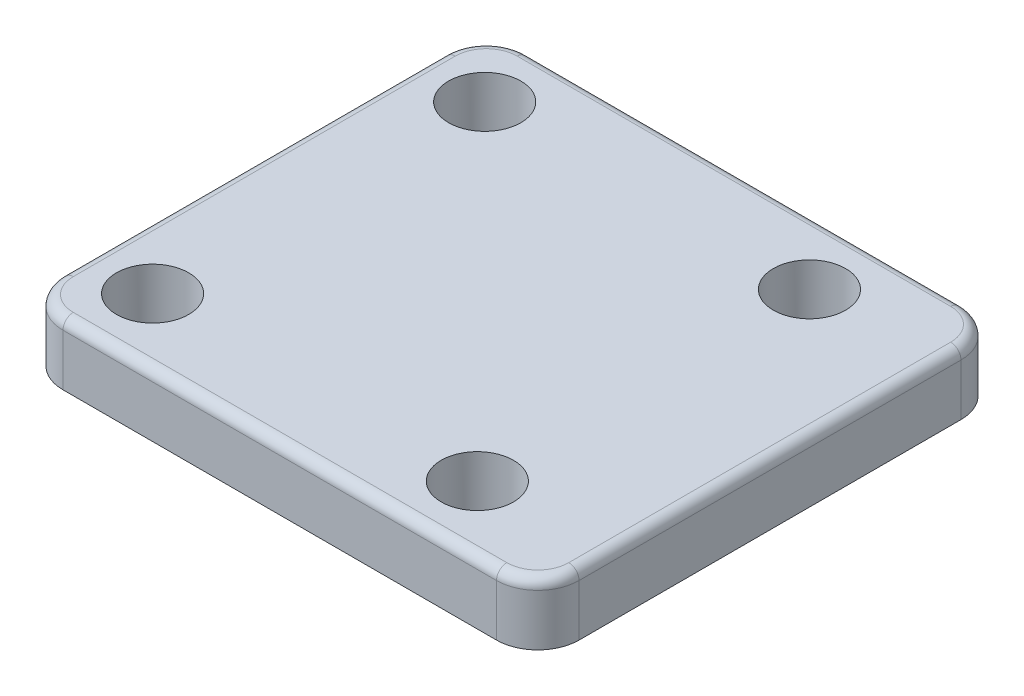
SolidWorks part; units mm, degrees
ref_plane "Front Plane" through (0, 0, 0) normal (0, 0, 1) x (1, 0, 0)
ref_plane "Top Plane" through (0, 0, 0) normal (0, 1, 0) x (1, 0, 0)
ref_plane "Right Plane" through (0, 0, 0) normal (1, 0, 0) x (0, 0, -1)
sketch "Sketch1" plane through (0, 0, 0) normal (0, 1, 0) x (1, 0, 0)
  line L1 (21, -22.5) -> (-21, -22.5)
  line L2 (25, -18.5) -> (25, 18.5)
  line L3 (21, 22.5) -> (-21, 22.5)
  line L4 (-25, -18.5) -> (-25, 18.5)
  line L5 (25, -22.5) -> (-25, 22.5) construction
  line L6 (25, 22.5) -> (-25, -22.5) construction
  arc A0 (-21, -22.5) -> (-25, -18.5) centre (-21, -18.5) cw
  arc A1 (21, -22.5) -> (25, -18.5) centre (21, -18.5) ccw
  arc A2 (25, 18.5) -> (21, 22.5) centre (21, 18.5) ccw
  arc A3 (-21, 22.5) -> (-25, 18.5) centre (-21, 18.5) ccw
  point P0 (0, 0)
  dimension "D3" = 4
  dimension "D1" = 50
  dimension "D2" = 45
extrude "Boss-Extrude1" add sketch "Sketch1" along normal mid plane 6
sketch "Sketch2" plane through (0, 3, 0) normal (0, 1, 0) x (1, 0, 0)
  line L0 (-25, 18.5) -> (-25, -18.5) construction
  line L1 (21, 22.5) -> (-21, 22.5) construction
  line L2 (19, -22.5) -> (-25, -22.5)
  line L3 (19, -22.5) -> (19, 22.5)
  line L4 (19, 22.5) -> (-25, 22.5)
  line L5 (-25, -22.5) -> (-25, 22.5)
  line L6 (19, -22.5) -> (-25, 22.5) construction
  line L7 (19, 22.5) -> (-25, -22.5) construction
  circle A0 centre (-3, 0) radius 22.5 construction
  circle A1 centre (-18.7301, 16.0877) radius 3.5
  circle A2 centre (12.7301, 16.0877) radius 3.5
  circle A3 centre (12.7301, -16.0877) radius 3.5
  circle A4 centre (-18.7301, -16.0877) radius 3.5
  dimension "D2" = 45
  dimension "D3" = 7
  dimension "D1" = 22
extrude "Cut-Extrude2" cut sketch "Sketch2" against normal through all both and the other way through all contours A4 | A1 | A2 | A3
fillet "Fillet1" radius 1 8 edges at (-23.8284, 3, -21.3284) (0, 3, -22.5) (23.8284, 3, -21.3284) (25, 3, 0) (23.8284, 3, 21.3284) (0, 3, 22.5) (-23.8284, 3, 21.3284) (-25, 3, 0)
sketch "Sketch3" plane through (0, -3, 0) normal (0, -1, 0) x (1, 0, 0)
  circle A0 centre (0, 0) radius 16
  dimension "D1" = 32
extrude "Boss-Extrude2" add sketch "Sketch3" along normal blind 2
chamfer "Chamfer1" distance 1 angle 45 1 edges at (0, -5, -16)
